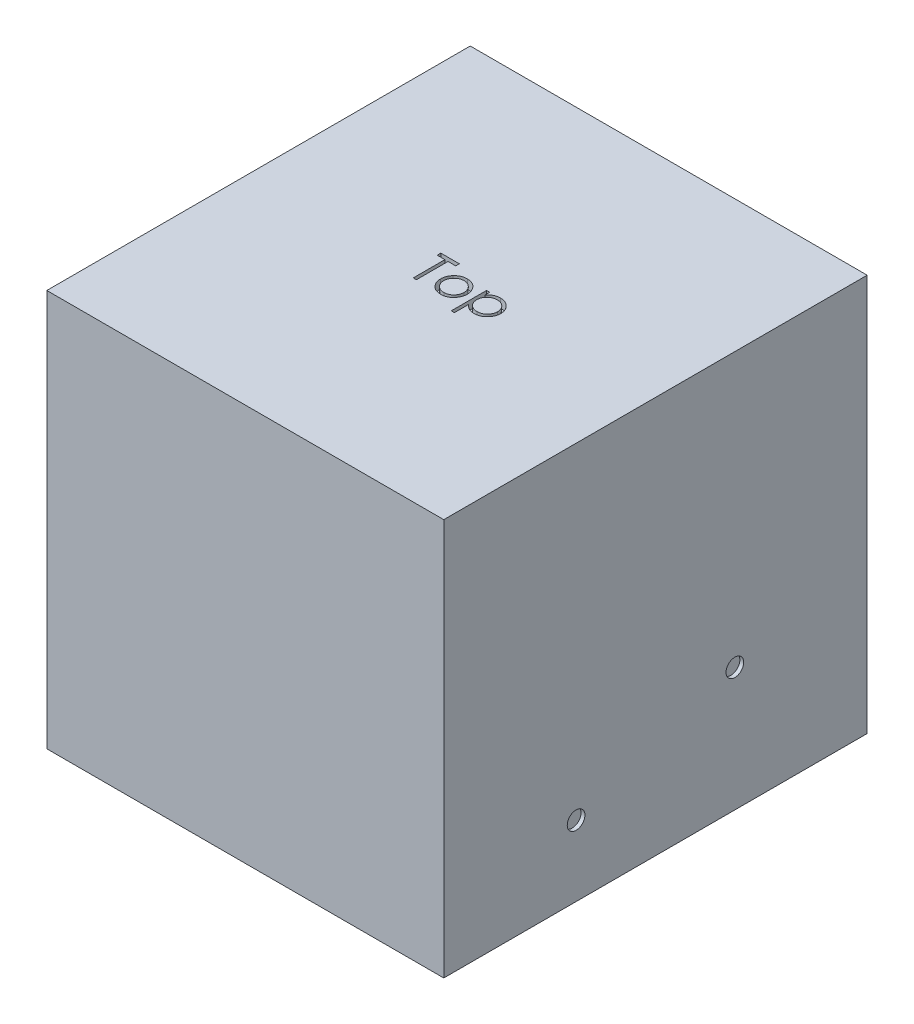
SolidWorks part; units mm, degrees
ref_plane "Front Plane" through (0, 0, 0) normal (0, 0, 1) x (1, 0, 0)
ref_plane "Top Plane" through (0, 0, 0) normal (0, 1, 0) x (1, 0, 0)
ref_plane "Right Plane" through (0, 0, 0) normal (1, 0, 0) x (0, 0, -1)
sketch "Sketch1" plane through (0, 0, 0) normal (0, 1, 0) x (1, 0, 0)
  line L1 (-138.7581, 216.6871) -> (86.2419, 216.6871)
  line L2 (-138.7581, 216.6871) -> (-138.7581, -23.3129)
  line L3 (-138.7581, -23.3129) -> (86.2419, -23.3129)
  line L4 (86.2419, 216.6871) -> (86.2419, -23.3129)
  dimension "D1" = 225
  dimension "D2" = 240
extrude "Boss-Extrude1" add sketch "Sketch1" along normal blind 225
ref_plane "Plane1" through (0, 225, 0) normal (0, 1, 0) x (1, 0, 0)
sketch "Sketch2" plane through (0, 225, 0) normal (0, 1, 0) x (1, 0, 0)
  line L0 (-90.1717, 96.6871) -> (37.6555, 96.6871) construction
  line L1 (-26.2581, 147.292) -> (-26.2581, -36.8194) construction
  line L2 (86.2419, -23.3129) -> (86.2419, 216.6871) construction
  line L3 (86.2419, 216.6871) -> (-138.7581, 216.6871) construction
  line L4 (-132.9681, 106.6871) -> (80.452, 106.6871) construction
  line L5 (-132.9681, 86.6871) -> (80.452, 86.6871) construction
  text T0 "Top" font "Century Gothic" height 20
  point P6 (86.2419, 96.6871)
  point P9 (-26.2581, 216.6871)
  point P15 (-26.2581, 106.6871)
  point P16 (-26.2581, 96.6871)
  point P17 (-60.9, 86.6871)
  point P18 (-45.6851, 86.6871)
  point P19 (0, 0)
  dimension "D1" = 10
  dimension "D2" = 213.42
extrude "Cut-Extrude1" cut sketch "Sketch2" along normal blind 5 and the other way blind 5
ref_plane "Plane2" through (86.2419, 0, 0) normal (1, 0, 0) x (0, 0, -1)
sketch "Sketch3" plane through (86.2419, 0, 0) normal (1, 0, 0) x (0, 0, -1)
  line L0 (35.8914, 40) -> (73.4005, 40) construction
  line L1 (-23.3129, 0) -> (216.6871, 0) construction
  line L2 (96.6871, 164.0225) -> (96.6871, -17.1571) construction
  line L3 (51.6871, 40) -> (141.6871, 40) construction
  line L4 (141.6871, 40) -> (141.6871, 70) construction
  circle A0 centre (141.6871, 70) radius 5.01
  circle A1 centre (51.6871, 40) radius 5.01
  point P6 (96.6871, 0)
  point P9 (96.6871, 40)
  dimension "D4" = 10.02
  dimension "D5" = 10.02
  dimension "D1" = 40
  dimension "D2" = 30
  dimension "D3" = 90
extrude "Cut-Extrude2" cut sketch "Sketch3" along normal blind 7 and the other way blind 2.2
ref_plane "Plane3" through (-26.2581, 0, 0) normal (-1, 0, 0) x (0, 0, 1)
mirror "Mirror2" about plane through (-26.2581, 0, 0) normal (-1, 0, 0) of "Cut-Extrude2"
